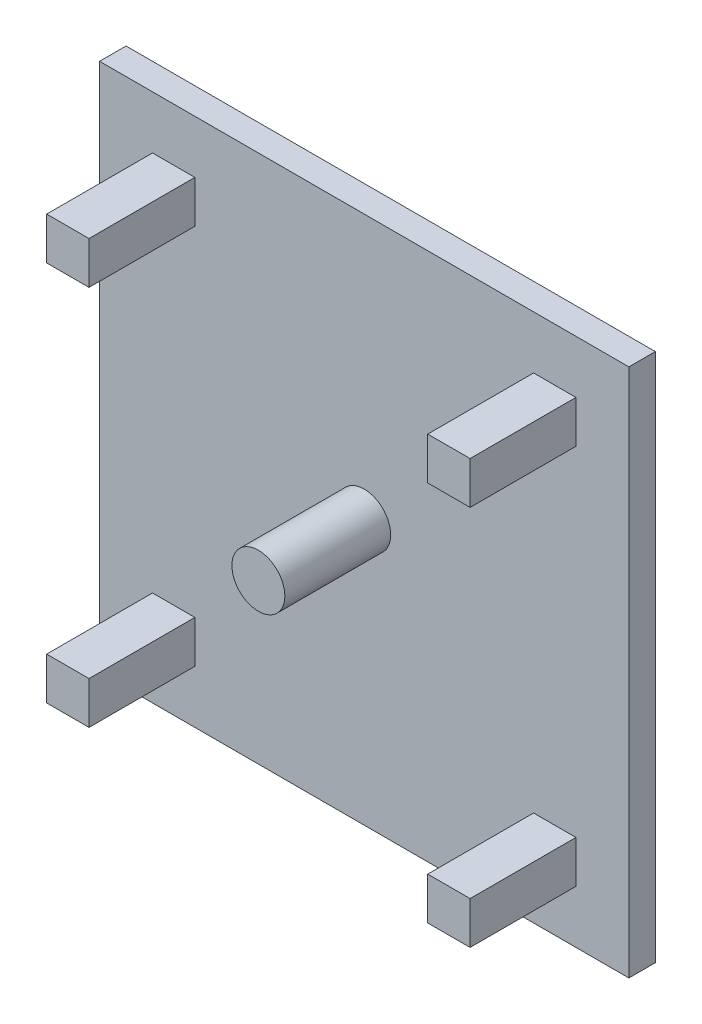
SolidWorks part; units mm, degrees
ref_plane "前视基准面" through (0, 0, 0) normal (0, 0, 1) x (1, 0, 0)
ref_plane "上视基准面" through (0, 0, 0) normal (0, 1, 0) x (1, 0, 0)
ref_plane "右视基准面" through (0, 0, 0) normal (1, 0, 0) x (0, 0, -1)
sketch "草图1" plane through (0, 0, 0) normal (0, 0, 1) x (1, 0, 0)
  line L1 (0, 0) -> (100, 0)
  line L2 (0, 0) -> (0, 100)
  line L3 (0, 100) -> (100, 100)
  line L4 (100, 0) -> (100, 100)
  dimension "D1" = 100
  dimension "D2" = 100
extrude "凸台-拉伸1" add sketch "草图1" along normal blind 25
sketch "草图2" plane through (0, 0, 25) normal (0, 0, 1) x (1, 0, 0)
  line L17 (10, 90) -> (18, 90)
  line L18 (10, 90) -> (10, 82)
  line L19 (10, 82) -> (18, 82)
  line L20 (0, 100) -> (0, 0)
  line L21 (0, 0) -> (100, 0)
  line L22 (100, 0) -> (100, 100)
  line L23 (100, 100) -> (0, 100)
  line L24 (0, 100) -> (0, 0)
  line L25 (0, 0) -> (100, 0)
  line L26 (100, 0) -> (100, 100)
  line L27 (100, 100) -> (0, 100)
  line L28 (18, 90) -> (18, 82)
  line L29 (90, 90) -> (82, 90)
  line L30 (90, 90) -> (90, 82)
  line L31 (90, 82) -> (82, 82)
  line L32 (82, 90) -> (82, 82)
  line L33 (10, 18) -> (18, 18)
  line L34 (10, 18) -> (10, 10)
  line L35 (10, 10) -> (18, 10)
  line L36 (18, 18) -> (18, 10)
  line L37 (82, 18) -> (90, 18)
  line L38 (82, 18) -> (82, 10)
  line L39 (82, 10) -> (90, 10)
  line L40 (90, 18) -> (90, 10)
  dimension "D1" = 0
  dimension "D2" = 10
  dimension "D3" = 10
  dimension "D4" = 8
  dimension "D5" = 8
  dimension "D6" = 8
  dimension "D7" = 8
  dimension "D8" = 8
  dimension "D9" = 8
  dimension "D10" = 8
  dimension "D11" = 8
  dimension "D12" = 10
  dimension "D13" = 10
  dimension "D14" = 10
  dimension "D15" = 10
  dimension "D16" = 10
  dimension "D17" = 10
extrude "切除-拉伸1" cut sketch "草图2" against normal offset from surface (20 mm away) 5 up to face at (50, 50, 0)
sketch "草图3" plane through (0, 0, 25) normal (0, 0, 1) x (1, 0, 0)
  line L0 (100, 100) -> (0, 100) construction
  line L2 (100, 0) -> (100, 100) construction
  circle A0 centre (50, 50) radius 5
  dimension "D3" = 10
  dimension "D1" = 50
  dimension "D2" = 50
extrude "凸台-拉伸2" add sketch "草图3" against normal up to next contours A0
